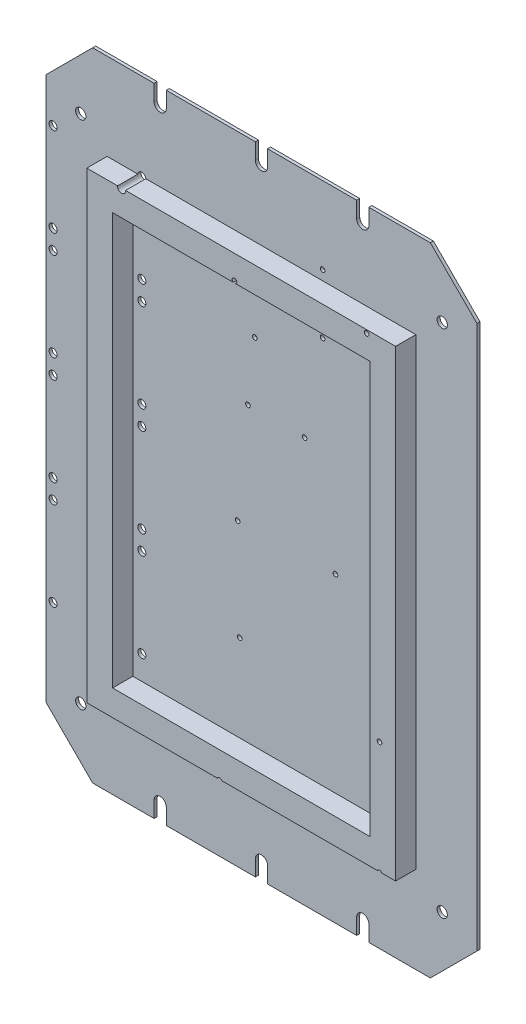
SolidWorks part; units mm, degrees
ref_plane "Front Plane" through (0, 0, 0) normal (0, 0, 1) x (1, 0, 0)
ref_plane "Top Plane" through (0, 0, 0) normal (0, 1, 0) x (1, 0, 0)
ref_plane "Right Plane" through (0, 0, 0) normal (1, 0, 0) x (0, 0, -1)
sketch "Sketch1" plane through (0, 0, 0) normal (0, 0, 1) x (1, 0, 0)
  line L0 (-106.3625, 134.1625) -> (-83.3625, 157.1625) construction
  line L1 (-106.3625, -157.1625) -> (106.3625, -157.1625)
  line L2 (-106.3625, -157.1625) -> (-106.3625, 157.1625)
  line L3 (-106.3625, 157.1625) -> (106.3625, 157.1625)
  line L4 (106.3625, -157.1625) -> (106.3625, 157.1625)
  line L5 (-106.3625, -157.1625) -> (106.3625, 157.1625) construction
  line L6 (-106.3625, 157.1625) -> (106.3625, -157.1625) construction
  line L8 (-50, -149.225) -> (50, -149.225) construction
  line L9 (-50, -149.225) -> (-50, 149.225) construction
  line L10 (-50, 149.225) -> (50, 149.225) construction
  line L11 (50, -149.225) -> (50, 149.225) construction
  line L12 (0, 149.225) -> (0, -149.225) construction
  line L13 (-50, 0) -> (50, 0) construction
  circle A0 centre (50, 149.225) radius 3
  point P0 (0, 0)
  point P8 (0, 0)
  point P13 (0, 149.225)
  point P14 (50, 152.225)
  dimension "Mounting Hole Diameter" = 6
  dimension "Height" = 314.325
  dimension "Width" = 212.725
  dimension "Chamfer Angle" = 45
  dimension "Chamfer Distance" = 23
  dimension "Mounting Hole Center to Center Height" = 298.45
  dimension "Mounting Hole Center to Center Width" = 100
  dimension "Mounting Hole Spacing" = 50
sketch "Sketch2" plane through (0, 0, 0) normal (1, 0, 0) x (0, 0, -1)
  line L0 (-0.75, 157.1625) -> (0.75, 157.1625) construction
  point P3 (0, 157.1625)
  dimension "Thickness" = 1.5
sketch "Sketch3" plane through (0, 0, 0) normal (0, 0, 1) x (1, 0, 0)
  line L0 (-106.3625, 134.1625) -> (-83.3625, 157.1625)
  line L1 (-83.3625, 157.1625) -> (83.3625, 157.1625)
  line L2 (-106.3625, 157.1625) -> (106.3625, 157.1625) construction
  line L3 (83.3625, 157.1625) -> (106.3625, 134.1625)
  line L4 (106.3625, -157.1625) -> (106.3625, 157.1625) construction
  line L5 (106.3625, 134.1625) -> (106.3625, -134.1625)
  line L6 (106.3625, -134.1625) -> (83.3625, -157.1625)
  line L7 (-106.3625, -157.1625) -> (106.3625, -157.1625) construction
  line L8 (83.3625, -157.1625) -> (-83.3625, -157.1625)
  line L9 (-83.3625, -157.1625) -> (-106.3625, -134.1625)
  line L10 (-106.3625, -157.1625) -> (-106.3625, 157.1625) construction
  line L11 (-106.3625, -134.1625) -> (-106.3625, 134.1625)
extrude "Boss-Extrude1" add sketch "Sketch3" against normal up to vertex (0.75 mm away) and the other way up to vertex (0.75 mm away) up to point (0, 157.1625, -0.75) other way up to point (0, 157.1625, 0.75)
sketch "Sketch4" plane through (0, 0, 0) normal (0, 0, 1) x (1, 0, 0)
  line L1 (53, 149.225) -> (53, 157.1625)
  line L3 (-106.3625, 157.1625) -> (106.3625, 157.1625) construction
  line L6 (53, 157.1625) -> (47, 157.1625)
  line L7 (47, 157.1625) -> (47, 149.225)
  circle A0 centre (50, 149.225) radius 3 construction
  arc A1 (47, 149.225) -> (53, 149.225) centre (50, 149.225) ccw
extrude "Cut-Extrude1" cut sketch "Sketch4" against normal through all both and the other way through all
pattern_linear "LPattern1" count 7 spacing 50 along (-1, 0, 0) of "Cut-Extrude1"
mirror "Mirror1" about plane through (0, 0, 0) normal (0, 1, 0) of "Cut-Extrude1", "LPattern1"
sketch "Sketch6" plane through (0, 0, -0.75) normal (0, 0, -1) x (-1, 0, 0)
  line L1 (-76.2, 114.3) -> (76.2, 114.3)
  line L2 (-76.2, 114.3) -> (-76.2, -114.3)
  line L3 (-76.2, -114.3) -> (76.2, -114.3)
  line L4 (76.2, 114.3) -> (76.2, -114.3)
  line L5 (-76.2, 114.3) -> (76.2, -114.3) construction
  line L6 (-76.2, -114.3) -> (76.2, 114.3) construction
  line L7 (-63.5, 101.6) -> (63.5, 101.6)
  line L8 (-63.5, 101.6) -> (-63.5, -101.6)
  line L9 (-63.5, -101.6) -> (63.5, -101.6)
  line L10 (63.5, 101.6) -> (63.5, -101.6)
  line L11 (-63.5, 101.6) -> (63.5, -101.6) construction
  line L12 (-63.5, -101.6) -> (63.5, 101.6) construction
  point P0 (0, 0)
  point P6 (0, 0)
  dimension "D1" = 152.4
  dimension "D2" = 12.7
  dimension "D3" = 12.7
  dimension "D4" = 228.6
extrude "Boss-Extrude2" add sketch "Sketch6" against normal blind 11.5
sketch "Sketch7" plane through (0, 0, -0.75) normal (0, 0, -1) x (-1, 0, 0)
  line L0 (-47, 157.1625) -> (-3, 157.1625) construction
  line L1 (-89.2175, 126.0475) -> (89.2175, 126.0475) construction
  line L2 (-89.2175, 126.0475) -> (-89.2175, -126.0475) construction
  line L3 (-89.2175, -126.0475) -> (89.2175, -126.0475) construction
  line L4 (89.2175, 126.0475) -> (89.2175, -126.0475) construction
  line L5 (83.3625, -157.1625) -> (53, -157.1625) construction
  line L6 (106.3625, 134.1625) -> (106.3625, -134.1625) construction
  line L7 (-106.3625, -134.1625) -> (-106.3625, 134.1625) construction
  circle A0 centre (89.2175, 126.0475) radius 2.54
  circle A1 centre (-89.2175, 126.0475) radius 2.54
  circle A2 centre (-89.2175, -126.0475) radius 2.54
  circle A3 centre (89.2175, -126.0475) radius 2.54
  dimension "D1" = 5.08
  dimension "D2" = 31.115
  dimension "D3" = 31.115
  dimension "D4" = 17.145
  dimension "D5" = 17.145
extrude "Cut-Extrude2" cut sketch "Sketch7" against normal through all
sketch "Sketch8" plane through (0, 0, -0.75) normal (0, 0, -1) x (-1, 0, 0)
  line L0 (-30.1625, 89.8625) -> (3.3375, 89.8625) construction
  line L1 (-30.1625, 119.0625) -> (3.3375, 119.0625) construction
  line L2 (-30.1625, 119.0625) -> (-30.1625, 102.5625) construction
  line L3 (-30.1625, 102.5625) -> (3.3375, 102.5625) construction
  line L4 (3.3375, 119.0625) -> (3.3375, 102.5625) construction
  line L5 (-30.1625, 89.8625) -> (-30.1625, 73.3625) construction
  line L6 (-30.1625, 73.3625) -> (3.3375, 73.3625) construction
  line L7 (3.3375, 89.8625) -> (3.3375, 73.3625) construction
  line L8 (-47, 157.1625) -> (-3, 157.1625) construction
  line L9 (-106.3625, -134.1625) -> (-106.3625, 134.1625) construction
  line L10 (-21.2725, 42.8625) -> (6.6675, 42.8625) construction
  line L11 (-61.9125, 112.7125) -> (-61.9125, 33.7125) construction
  line L12 (-68.2625, -58.7375) -> (10.7375, -58.7375) construction
  line L13 (-68.2625, -58.7375) -> (-68.2625, -114.7375) construction
  line L14 (-68.2625, -114.7375) -> (10.7375, -114.7375) construction
  line L15 (10.7375, -58.7375) -> (10.7375, -114.7375) construction
  circle A0 centre (-30.1625, 119.0625) radius 1.15
  circle A1 centre (3.3375, 102.5625) radius 1.15
  circle A2 centre (-30.1625, 89.8625) radius 1.15
  circle A3 centre (3.3375, 73.3625) radius 1.15
  circle A4 centre (-21.2725, 42.8625) radius 1.15
  circle A5 centre (6.6675, 42.8625) radius 1.15
  circle A6 centre (-36.5125, -7.9375) radius 1.15
  circle A7 centre (11.7475, -9.2075) radius 1.15
  circle A8 centre (-68.2625, -58.7375) radius 1.15
  circle A9 centre (10.7375, -58.7375) radius 1.15
  circle A10 centre (10.7375, -114.7375) radius 1.15
  circle A11 centre (-68.2625, -114.7375) radius 1.15
  circle A12 centre (-61.9125, 112.7125) radius 1.15
  circle A13 centre (-61.9125, 33.7125) radius 1.15
  dimension "D1" = 2.3
  dimension "D4" = 27.94
  dimension "D5" = 15.24
  dimension "D6" = 5.08
  dimension "D10" = 1.27
  dimension "D12" = 69.85
  dimension "D18" = 79
  dimension "D19" = 44.45
  dimension "D20" = 44.45
  dimension "D2" = 16.5
  dimension "D3" = 33.5
  dimension "D7" = 38.1
  dimension "D8" = 12.7
  dimension "D9" = 76.2
  dimension "D11" = 114.3
  dimension "D13" = 50.8
  dimension "D14" = 79
  dimension "D15" = 56
  dimension "D16" = 38.1
  dimension "D17" = 215.9
extrude "Cut-Extrude3" cut sketch "Sketch8" against normal through all both and the other way through all
sketch "Sketch10" plane through (0, 0, -0.75) normal (0, 0, -1) x (-1, 0, 0)
  line L0 (55.5625, 116.054) -> (55.5625, 68.302) construction
  line L1 (57.0865, 66.778) -> (104.8385, 66.778) construction
  line L2 (106.3625, 68.302) -> (106.3625, 116.054) construction
  line L3 (104.8385, 117.578) -> (57.0865, 117.578) construction
  line L4 (55.5625, 62.714) -> (55.5625, 14.962) construction
  line L5 (57.0865, 13.438) -> (104.8385, 13.438) construction
  line L6 (106.3625, 14.962) -> (106.3625, 62.714) construction
  line L7 (104.8385, 64.238) -> (57.0865, 64.238) construction
  line L8 (55.5625, 9.374) -> (55.5625, -38.378) construction
  line L9 (57.0865, -39.902) -> (104.8385, -39.902) construction
  line L10 (106.3625, -38.378) -> (106.3625, 9.374) construction
  line L11 (104.8385, 10.898) -> (57.0865, 10.898) construction
  line L12 (55.5625, -43.966) -> (55.5625, -91.718) construction
  line L13 (57.0865, -93.242) -> (104.8385, -93.242) construction
  line L14 (106.3625, -91.718) -> (106.3625, -43.966) construction
  line L15 (104.8385, -42.442) -> (57.0865, -42.442) construction
  line L16 (55.5625, 116.054) -> (55.5625, 68.302) construction
  line L17 (57.0865, 66.778) -> (104.8385, 66.778) construction
  line L18 (106.3625, 68.302) -> (106.3625, 116.054) construction
  line L19 (104.8385, 117.578) -> (57.0865, 117.578) construction
  line L20 (55.5625, 62.714) -> (55.5625, 14.962) construction
  line L21 (57.0865, 13.438) -> (104.8385, 13.438) construction
  line L22 (106.3625, 14.962) -> (106.3625, 62.714) construction
  line L23 (104.8385, 64.238) -> (57.0865, 64.238) construction
  line L24 (55.5625, 9.374) -> (55.5625, -38.378) construction
  line L25 (57.0865, -39.902) -> (104.8385, -39.902) construction
  line L26 (106.3625, -38.378) -> (106.3625, 9.374) construction
  line L27 (104.8385, 10.898) -> (57.0865, 10.898) construction
  line L28 (55.5625, -43.966) -> (55.5625, -91.718) construction
  line L29 (57.0865, -93.242) -> (104.8385, -93.242) construction
  line L30 (106.3625, -91.718) -> (106.3625, -43.966) construction
  line L31 (104.8385, -42.442) -> (57.0865, -42.442) construction
  arc A0 (55.5625, 68.302) -> (57.0865, 66.778) centre (57.0865, 68.302) ccw construction
  arc A1 (104.8385, 66.778) -> (106.3625, 68.302) centre (104.8385, 68.302) ccw construction
  arc A2 (106.3625, 116.054) -> (104.8385, 117.578) centre (104.8385, 116.054) ccw construction
  arc A3 (57.0865, 117.578) -> (55.5625, 116.054) centre (57.0865, 116.054) ccw construction
  arc A4 (55.5625, 14.962) -> (57.0865, 13.438) centre (57.0865, 14.962) ccw construction
  arc A5 (104.8385, 13.438) -> (106.3625, 14.962) centre (104.8385, 14.962) ccw construction
  arc A6 (106.3625, 62.714) -> (104.8385, 64.238) centre (104.8385, 62.714) ccw construction
  arc A7 (57.0865, 64.238) -> (55.5625, 62.714) centre (57.0865, 62.714) ccw construction
  arc A8 (55.5625, -38.378) -> (57.0865, -39.902) centre (57.0865, -38.378) ccw construction
  arc A9 (104.8385, -39.902) -> (106.3625, -38.378) centre (104.8385, -38.378) ccw construction
  arc A10 (106.3625, 9.374) -> (104.8385, 10.898) centre (104.8385, 9.374) ccw construction
  arc A11 (57.0865, 10.898) -> (55.5625, 9.374) centre (57.0865, 9.374) ccw construction
  arc A12 (55.5625, -91.718) -> (57.0865, -93.242) centre (57.0865, -91.718) ccw construction
  arc A13 (104.8385, -93.242) -> (106.3625, -91.718) centre (104.8385, -91.718) ccw construction
  arc A14 (106.3625, -43.966) -> (104.8385, -42.442) centre (104.8385, -43.966) ccw construction
  arc A15 (57.0865, -42.442) -> (55.5625, -43.966) centre (57.0865, -43.966) ccw construction
  arc A16 (55.5625, 68.302) -> (57.0865, 66.778) centre (57.0865, 68.302) ccw construction
  arc A17 (104.8385, 66.778) -> (106.3625, 68.302) centre (104.8385, 68.302) ccw construction
  arc A18 (106.3625, 116.054) -> (104.8385, 117.578) centre (104.8385, 116.054) ccw construction
  arc A19 (57.0865, 117.578) -> (55.5625, 116.054) centre (57.0865, 116.054) ccw construction
  arc A20 (55.5625, 14.962) -> (57.0865, 13.438) centre (57.0865, 14.962) ccw construction
  arc A21 (104.8385, 13.438) -> (106.3625, 14.962) centre (104.8385, 14.962) ccw construction
  arc A22 (106.3625, 62.714) -> (104.8385, 64.238) centre (104.8385, 62.714) ccw construction
  arc A23 (57.0865, 64.238) -> (55.5625, 62.714) centre (57.0865, 62.714) ccw construction
  arc A24 (55.5625, -38.378) -> (57.0865, -39.902) centre (57.0865, -38.378) ccw construction
  arc A25 (104.8385, -39.902) -> (106.3625, -38.378) centre (104.8385, -38.378) ccw construction
  arc A26 (106.3625, 9.374) -> (104.8385, 10.898) centre (104.8385, 9.374) ccw construction
  arc A27 (57.0865, 10.898) -> (55.5625, 9.374) centre (57.0865, 9.374) ccw construction
  arc A28 (55.5625, -91.718) -> (57.0865, -93.242) centre (57.0865, -91.718) ccw construction
  arc A29 (104.8385, -93.242) -> (106.3625, -91.718) centre (104.8385, -91.718) ccw construction
  arc A30 (106.3625, -43.966) -> (104.8385, -42.442) centre (104.8385, -43.966) ccw construction
  arc A31 (57.0865, -42.442) -> (55.5625, -43.966) centre (57.0865, -43.966) ccw construction
  arc A32 (59.0677, -91.718) -> (59.0677, -87.7556) centre (59.0677, -89.7368) ccw construction
  arc A33 (59.0677, -87.7556) -> (59.0677, -91.718) centre (59.0677, -89.7368) ccw construction
  arc A34 (59.0677, -91.718) -> (59.0677, -87.7556) centre (59.0677, -89.7368) ccw
  arc A35 (59.0677, -87.7556) -> (59.0677, -91.718) centre (59.0677, -89.7368) ccw
  arc A36 (59.0677, -38.378) -> (59.0677, -34.4156) centre (59.0677, -36.3968) ccw construction
  arc A37 (59.0677, -34.4156) -> (59.0677, -38.378) centre (59.0677, -36.3968) ccw construction
  arc A38 (59.0677, -47.903) -> (59.0677, -43.9406) centre (59.0677, -45.9218) ccw construction
  arc A39 (59.0677, -43.9406) -> (59.0677, -47.903) centre (59.0677, -45.9218) ccw construction
  arc A40 (59.0677, -38.378) -> (59.0677, -34.4156) centre (59.0677, -36.3968) ccw
  arc A41 (59.0677, -34.4156) -> (59.0677, -38.378) centre (59.0677, -36.3968) ccw
  arc A42 (59.0677, -47.903) -> (59.0677, -43.9406) centre (59.0677, -45.9218) ccw
  arc A43 (59.0677, -43.9406) -> (59.0677, -47.903) centre (59.0677, -45.9218) ccw
  arc A44 (59.0677, 5.437) -> (59.0677, 9.3994) centre (59.0677, 7.4182) ccw construction
  arc A45 (59.0677, 9.3994) -> (59.0677, 5.437) centre (59.0677, 7.4182) ccw construction
  arc A46 (59.0677, 5.437) -> (59.0677, 9.3994) centre (59.0677, 7.4182) ccw
  arc A47 (59.0677, 9.3994) -> (59.0677, 5.437) centre (59.0677, 7.4182) ccw
  arc A48 (59.0677, 14.962) -> (59.0677, 18.9244) centre (59.0677, 16.9432) ccw construction
  arc A49 (59.0677, 18.9244) -> (59.0677, 14.962) centre (59.0677, 16.9432) ccw construction
  arc A50 (59.0677, 14.962) -> (59.0677, 18.9244) centre (59.0677, 16.9432) ccw
  arc A51 (59.0677, 18.9244) -> (59.0677, 14.962) centre (59.0677, 16.9432) ccw
  arc A52 (59.0677, 58.777) -> (59.0677, 62.7394) centre (59.0677, 60.7582) ccw construction
  arc A53 (59.0677, 62.7394) -> (59.0677, 58.777) centre (59.0677, 60.7582) ccw construction
  arc A54 (59.0677, 68.302) -> (59.0677, 72.2644) centre (59.0677, 70.2832) ccw construction
  arc A55 (59.0677, 72.2644) -> (59.0677, 68.302) centre (59.0677, 70.2832) ccw construction
  arc A56 (59.0677, 58.777) -> (59.0677, 62.7394) centre (59.0677, 60.7582) ccw
  arc A57 (59.0677, 62.7394) -> (59.0677, 58.777) centre (59.0677, 60.7582) ccw
  arc A58 (59.0677, 68.302) -> (59.0677, 72.2644) centre (59.0677, 70.2832) ccw
  arc A59 (59.0677, 72.2644) -> (59.0677, 68.302) centre (59.0677, 70.2832) ccw
  arc A60 (59.0677, 112.117) -> (59.0677, 116.0794) centre (59.0677, 114.0982) ccw construction
  arc A61 (59.0677, 116.0794) -> (59.0677, 112.117) centre (59.0677, 114.0982) ccw construction
  arc A62 (59.0677, 112.117) -> (59.0677, 116.0794) centre (59.0677, 114.0982) ccw
  arc A63 (59.0677, 116.0794) -> (59.0677, 112.117) centre (59.0677, 114.0982) ccw
  arc A64 (102.8827, 68.302) -> (102.8827, 72.2644) centre (102.8827, 70.2832) ccw construction
  arc A65 (102.8827, 72.2644) -> (102.8827, 68.302) centre (102.8827, 70.2832) ccw construction
  arc A66 (102.8827, 112.117) -> (102.8827, 116.0794) centre (102.8827, 114.0982) ccw construction
  arc A67 (102.8827, 116.0794) -> (102.8827, 112.117) centre (102.8827, 114.0982) ccw construction
  arc A68 (102.8827, 68.302) -> (102.8827, 72.2644) centre (102.8827, 70.2832) ccw
  arc A69 (102.8827, 72.2644) -> (102.8827, 68.302) centre (102.8827, 70.2832) ccw
  arc A70 (102.8827, 112.117) -> (102.8827, 116.0794) centre (102.8827, 114.0982) ccw
  arc A71 (102.8827, 116.0794) -> (102.8827, 112.117) centre (102.8827, 114.0982) ccw
  arc A72 (102.8827, 14.962) -> (102.8827, 18.9244) centre (102.8827, 16.9432) ccw construction
  arc A73 (102.8827, 18.9244) -> (102.8827, 14.962) centre (102.8827, 16.9432) ccw construction
  arc A74 (102.8827, 58.777) -> (102.8827, 62.7394) centre (102.8827, 60.7582) ccw construction
  arc A75 (102.8827, 62.7394) -> (102.8827, 58.777) centre (102.8827, 60.7582) ccw construction
  arc A76 (102.8827, 14.962) -> (102.8827, 18.9244) centre (102.8827, 16.9432) ccw
  arc A77 (102.8827, 18.9244) -> (102.8827, 14.962) centre (102.8827, 16.9432) ccw
  arc A78 (102.8827, 58.777) -> (102.8827, 62.7394) centre (102.8827, 60.7582) ccw
  arc A79 (102.8827, 62.7394) -> (102.8827, 58.777) centre (102.8827, 60.7582) ccw
  arc A80 (102.8827, -38.378) -> (102.8827, -34.4156) centre (102.8827, -36.3968) ccw construction
  arc A81 (102.8827, -34.4156) -> (102.8827, -38.378) centre (102.8827, -36.3968) ccw construction
  arc A82 (102.8827, 5.437) -> (102.8827, 9.3994) centre (102.8827, 7.4182) ccw construction
  arc A83 (102.8827, 9.3994) -> (102.8827, 5.437) centre (102.8827, 7.4182) ccw construction
  arc A84 (102.8827, -38.378) -> (102.8827, -34.4156) centre (102.8827, -36.3968) ccw
  arc A85 (102.8827, -34.4156) -> (102.8827, -38.378) centre (102.8827, -36.3968) ccw
  arc A86 (102.8827, 5.437) -> (102.8827, 9.3994) centre (102.8827, 7.4182) ccw
  arc A87 (102.8827, 9.3994) -> (102.8827, 5.437) centre (102.8827, 7.4182) ccw
  arc A88 (102.8827, -47.903) -> (102.8827, -43.9406) centre (102.8827, -45.9218) ccw construction
  arc A89 (102.8827, -43.9406) -> (102.8827, -47.903) centre (102.8827, -45.9218) ccw construction
  arc A90 (102.8827, -91.718) -> (102.8827, -87.7556) centre (102.8827, -89.7368) ccw construction
  arc A91 (102.8827, -87.7556) -> (102.8827, -91.718) centre (102.8827, -89.7368) ccw construction
  arc A92 (102.8827, -47.903) -> (102.8827, -43.9406) centre (102.8827, -45.9218) ccw
  arc A93 (102.8827, -43.9406) -> (102.8827, -47.903) centre (102.8827, -45.9218) ccw
  arc A94 (102.8827, -91.718) -> (102.8827, -87.7556) centre (102.8827, -89.7368) ccw
  arc A95 (102.8827, -87.7556) -> (102.8827, -91.718) centre (102.8827, -89.7368) ccw
extrude "Cut-Extrude4" cut sketch "Sketch10" against normal through all
equation "\"D3@LPattern1\"=\"Mounting Hole Spacing@Sketch1\""
equation "\"D1@LPattern1\"=(\"Mounting Hole Center to Center Height@Sketch1\"/\"Mounting Hole Spacing@Sketch1\")+1"
